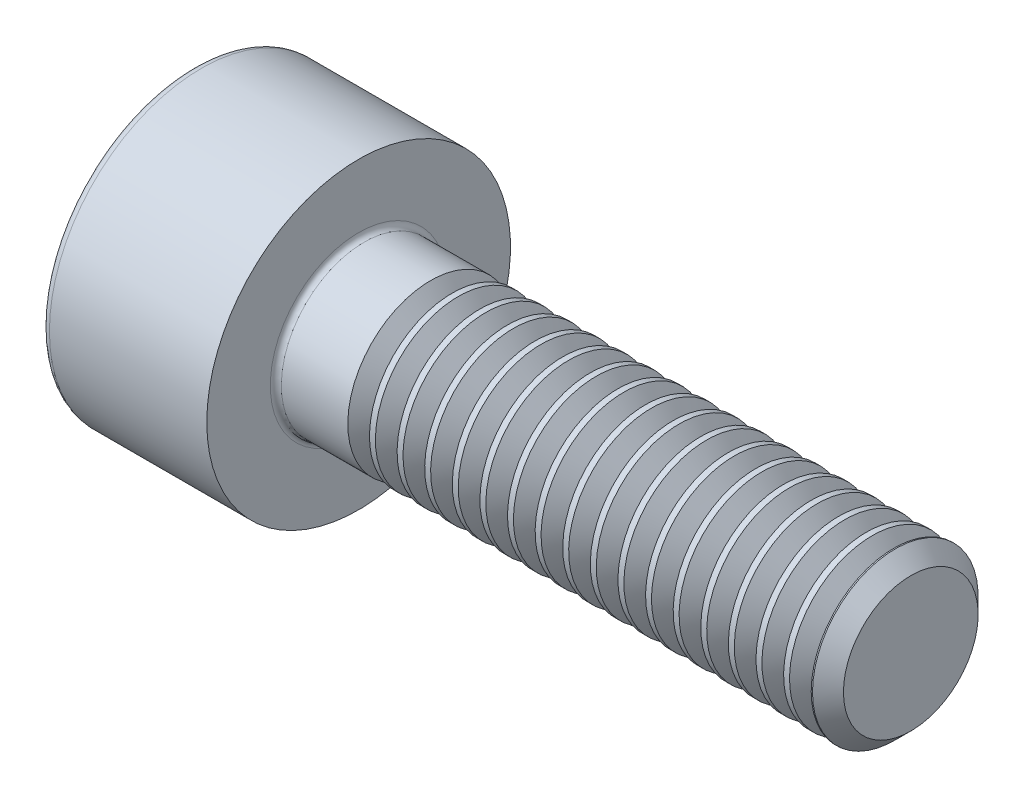
SolidWorks part; units mm, degrees
revolve "Base-Revolve" add sketch "BodySke"
sketch "BodySke" plane through (0, 0, 0) normal (0, 0, 1) x (1, 0, 0)
  line L0 (0, 0) -> (0, 2.75)
  line L1 (0, 2.75) -> (3, 2.75)
  line L2 (3, 2.75) -> (3, 1.5)
  line L3 (3, 1.5) -> (12.7195, 1.5)
  line L4 (13, 1.2195) -> (13, 0)
  line L5 (13, 0) -> (0, 0)
  line L6 (-31.75, 0) -> (127, 0) construction
  line L8 (13, 1.2195) -> (12.7195, 1.5)
  line L10 (13, -1.2195) -> (12.7195, -1.5) construction
  line L11 (3.5, 9.525) -> (3.5, 3.175) construction
  line L12 (3, 9.525) -> (3, 3.175) construction
  line L13 (-47, 9.525) -> (-47, 3.175) construction
  dimension "Head_ht" = 3
  dimension "Length" = 10
  dimension "Body_ch_ang" = 45
  dimension "Diameter" = 3
  dimension "Minor_dia" = 2.439
  dimension "Advance" = 0.5
  dimension "Thread_nom" = 10
  dimension "Thread_length" = 60
  dimension "Head_dia" = 5.5
cosmetic thread "ThreadCosmetic" [suppressed]
fillet "Fillet1" radius 0.1 1 edges at (3, 0, 1.5)
fillet "Fillet2" radius 0.15 1 edges at (0, 0, 2.75)
ref_plane "Plane1" through (0, 0, 0) normal (0, 0, 1) x (1, 0, 0)
ref_plane "Plane2" through (0, 0, 0) normal (0, 1, 0) x (1, 0, 0)
ref_plane "Plane3" through (0, 0, 0) normal (1, 0, 0) x (0, 0, -1)
other "Configuration Table"
sketch "Sketch2" plane through (0, 0, 0) normal (0, 0, 1) x (1, 0, 0)
  line L0 (0, 1.28) -> (1.3, 1.28)
  line L1 (1.3, 1.28) -> (2.039, 0)
  line L2 (-31.75, 0) -> (127, 0) construction
  line L3 (2.039, 0) -> (0, 0)
  line L4 (0, 0) -> (0, 1.28)
  line L6 (0, 0) -> (47.625, 0) construction
  dimension "D1" = 1.28
  dimension "D2" = 60
  dimension "Depth" = 1.3
revolve "Hex-PreBroach" cut sketch "Sketch2" angle 360 about L6
sketch "Sketch3" plane through (0, 0, 0) normal (-1, 0, 0) x (0, 0.5, 0.866)
  line L0 (0.739, 1.28) -> (-0.739, 1.28)
  line L1 (-0.739, 1.28) -> (-1.478, 0)
  line L2 (0.739, 1.28) -> (1.478, 0)
  line L3 (0.739, -1.28) -> (1.478, 0)
  line L4 (0.739, -1.28) -> (-0.739, -1.28)
  line L5 (-0.739, -1.28) -> (-1.478, 0)
  dimension "D1" = 1.28
  dimension "D2" = 1.28
  dimension "Hex_size" = 2.56
extrude "Hex" cut sketch "Sketch3" against normal blind 1.3
sketch "ThdSchSke" plane through (0, 0, 0) normal (0, 0, 1) x (1, 0, 0)
  line L0 (4.5, -1.2195) -> (4.3036, -1.5)
  line L1 (4.5, -1.2195) -> (4.6964, -1.5)
  line L2 (4.6964, -1.5) -> (4.6964, -1.875)
  line L3 (-3.175, 0) -> (5.1513, 0) construction
  line L4 (0, 2.6) -> (0, -2.6) construction
  line L5 (4.6964, -1.875) -> (4.3036, -1.875)
  line L6 (4.3036, -1.875) -> (4.3036, -1.5)
  dimension "Thread_minor" = 2.439
  dimension "Diameter" = 3
  dimension "Start" = 4.5
revolve "ThreadSchematic" cut sketch "ThdSchSke" angle 360 about L3
pattern_linear "ThdSchPat" count 17 spacing 0.5 along (1, 0, 0) of "ThreadSchematic"
equation "\"D2@Sketch3\" = \"Hex_size@Sketch3\" / 2"
equation "\"D1@Sketch3\" = \"Hex_size@Sketch3\" / 2"
equation "\"D1@Sketch2\" = \"Hex_size@Sketch3\" / 2"
equation "\"Thread_minor@ThreadCosmetic\"  =  \"Minor_dia@BodySke\""
equation "\"Depth@Sketch2\" =  \"Key_eng@Hex\""
equation "\"Thread_length@ThreadCosmetic\" = ((sgn( (\"Length@BodySke\" - \"Advance@BodySke\" * 3.0) - \"Thread_nom@BodySke\" )-1)*( (\"Length@BodySke\" - \"Advance@BodySke\" * 3.0) - \"Thread_nom@BodySke\" ))/-2+ \"Thread_nom@BodySke\""
equation "\"Thread_minor@ThdSchSke\" = \"Minor_dia@BodySke\""
equation "\"Diameter@ThdSchSke\" = \"Diameter@BodySke\""
equation "\"Overcut@ThdSchSke\" = \"Diameter@BodySke\" * 1.25"
equation "\"Start@ThdSchSke\" = \"Head_ht@BodySke\" + \"Length@BodySke\" - \"Thread_length@ThreadCosmetic\"  '---Non-countersunk---"
equation "\"Num_threads@ThdSchPat\" = int( \"Thread_length@ThreadCosmetic\" / \"Advance@BodySke\" + 0.999 )  + 1"
equation "\"Advance@ThdSchPat\" = \"Thread_length@ThreadCosmetic\" /  (\"Num_threads@ThdSchPat\" - 1) 'relax it"
equation "\"Num_threads@ThdSchPat\" = \"Num_threads@ThdSchPat\" - sgn( \"Num_threads@ThdSchPat\" - 1) '---chamfered tips only---"
